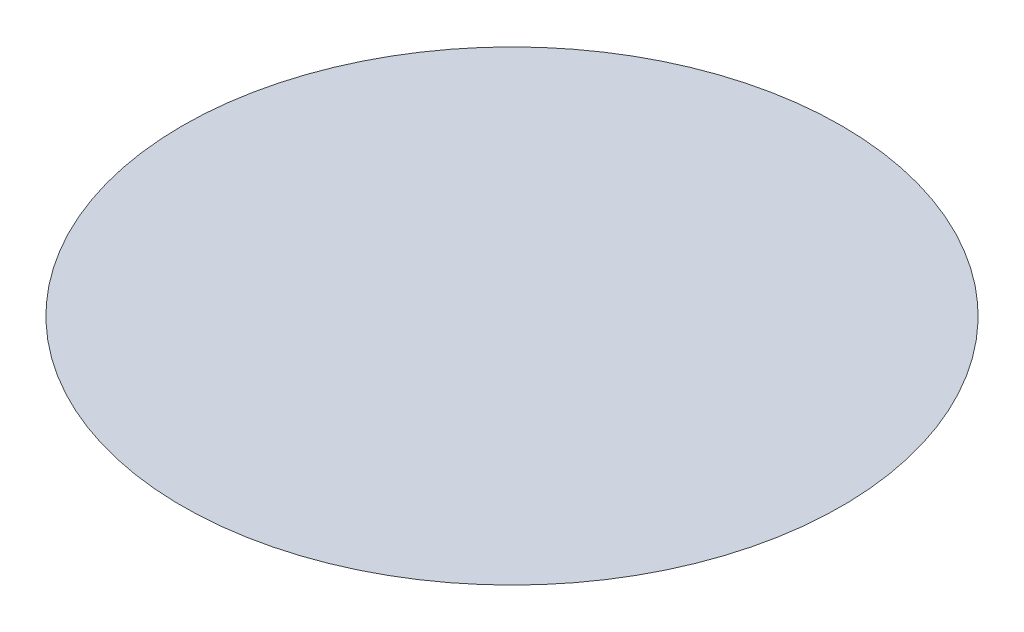
SolidWorks part; units mm, degrees
material "Alloy Steel"
ref_plane "Front Plane" through (0, 0, 0) normal (0, 0, 1) x (1, 0, 0)
ref_plane "Top Plane" through (0, 0, 0) normal (0, 1, 0) x (1, 0, 0)
ref_plane "Right Plane" through (0, 0, 0) normal (1, 0, 0) x (0, 0, -1)
sketch "Sketch1" plane through (0, 0, 0) normal (0, 0, 1) x (1, 0, 0)
  line L0 (0, 0) -> (0, 32)
  line L1 (0, 32) -> (108.5247, 32)
  arc A0 (0, 0) -> (108.5247, 32) centre (0, 200.025) ccw
  dimension "D1" = 200.025
  dimension "D2" = 32
revolve "Revolve1" add sketch "Sketch1" angle 360 about L0
